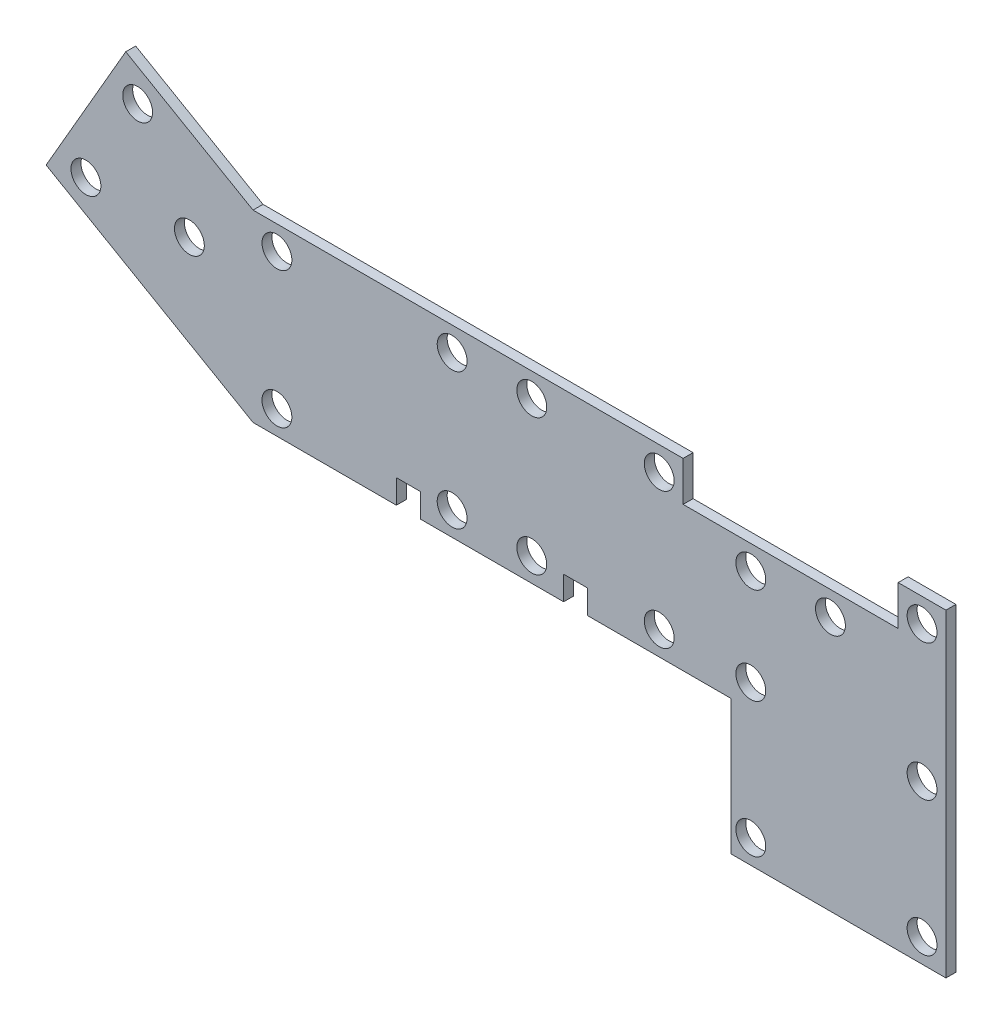
SolidWorks part; units mm, degrees
material "1023 Carbon Steel Sheet (SS)"
ref_plane "Front Plane" through (0, 0, 0) normal (0, 0, 1) x (1, 0, 0)
ref_plane "Top Plane" through (0, 0, 0) normal (0, 1, 0) x (1, 0, 0)
ref_plane "Right Plane" through (0, 0, 0) normal (1, 0, 0) x (0, 0, -1)
sketch "Sketch1" plane through (0, 0, 0) normal (0, 0, 1) x (1, 0, 0)
  line L0 (0, 0) -> (-40.5911, 23.4353)
  line L1 (-40.5911, 23.4353) -> (-65.9911, -20.5588)
  line L2 (-65.9911, -20.5588) -> (0, -58.6588)
  line L3 (0, -58.6588) -> (45.72, -58.6588)
  line L4 (45.72, -58.6588) -> (45.72, -51.0388)
  line L5 (45.72, -51.0388) -> (53.34, -51.0388)
  line L6 (53.34, -51.0388) -> (53.34, -58.6588)
  line L7 (53.34, -58.6588) -> (99.06, -58.6588)
  line L8 (99.06, -58.6588) -> (99.06, -51.0388)
  line L9 (99.06, -51.0388) -> (106.68, -51.0388)
  line L10 (106.68, -51.0388) -> (106.68, -58.6588)
  line L11 (106.68, -58.6588) -> (152.4, -58.6588)
  line L12 (152.4, -58.6588) -> (152.4, -101.6)
  line L13 (152.4, -101.6) -> (220.98, -101.6)
  line L14 (220.98, -101.6) -> (220.98, 0)
  line L15 (220.98, 0) -> (205.74, 0)
  line L16 (205.74, 0) -> (205.74, -12.7)
  line L17 (205.74, -12.7) -> (137.16, -12.7)
  line L18 (137.16, -12.7) -> (137.16, 0)
  line L19 (137.16, 0) -> (99.06, 0)
  line L23 (99.06, 0) -> (0, 0)
  circle A1 centre (-20.2956, -17.6117) radius 4.7625
  circle A2 centre (-53.2911, -17.6117) radius 4.7625
  circle A3 centre (-36.7934, 10.9633) radius 4.7625
  circle A4 centre (-36.7934, -8.0867) radius 19.05 construction
  circle A5 centre (7.62, -51.0388) radius 4.7625
  circle A6 centre (7.62, -7.62) radius 4.7625
  circle A7 centre (63.5, -7.62) radius 4.7625
  circle A8 centre (88.9, -7.62) radius 4.7625
  circle A9 centre (129.54, -7.62) radius 4.7625
  circle A10 centre (88.9, -51.0388) radius 4.7625
  circle A11 centre (63.5, -51.0388) radius 4.7625
  circle A12 centre (129.54, -51.0388) radius 4.7625
  circle A13 centre (158.75, -20.32) radius 4.7625
  circle A14 centre (184.15, -20.32) radius 4.7625
  circle A15 centre (213.36, -7.62) radius 4.7625
  circle A16 centre (213.36, -93.98) radius 4.7625
  circle A17 centre (158.75, -93.98) radius 4.7625
  circle A18 centre (213.36, -51.0388) radius 4.7625
  circle A19 centre (158.75, -51.0388) radius 4.7625
  point P3 (-36.7934, -8.0867)
  point P24 (171.45, -12.7)
  point P28 (-53.2911, 1.4383)
  point P33 (76.2, -58.6588)
  dimension "D18" = 9.525
  dimension "D21" = 3
  dimension "D16" = 38.1
  dimension "D17" = 7.62
  dimension "D1" = 30
  dimension "D2" = 76.2
  dimension "D3" = 50.8
  dimension "D4" = 76.2
  dimension "D5" = 68.58
  dimension "D6" = 7.62
  dimension "D7" = 7.62
  dimension "D8" = 45.72
  dimension "D9" = 152.4
  dimension "D10" = 7.62
  dimension "D11" = 19.05
  dimension "D12" = 38.1
  dimension "D13" = 101.6
  dimension "D14" = 15.24
  dimension "D15" = 12.7
  dimension "D19" = 19.05
  dimension "D20" = 25.4
  dimension "D22" = 7.62
  dimension "D23" = 7.62
  dimension "D24" = 12.7
  dimension "D25" = 12.7
  dimension "D26" = 7.62
  dimension "D27" = 7.62
  dimension "D28" = 12.7
  dimension "D29" = 12.7
  dimension "D30" = 7.62
  dimension "D31" = 7.62
  dimension "D32" = 7.62
extrude "Boss-Extrude1" add sketch "Sketch1" along normal blind 3.175 contours L19 L23 L0 L1 L2 L3 L4 L5 L6 L7 L8 L9 L10 L11 L12 L13 L14 L15 L16 L17 L18 A19 A18 A17 A16 A15 A14 A13 A12 A11 A10 A9 A8 A7 A6 A5
